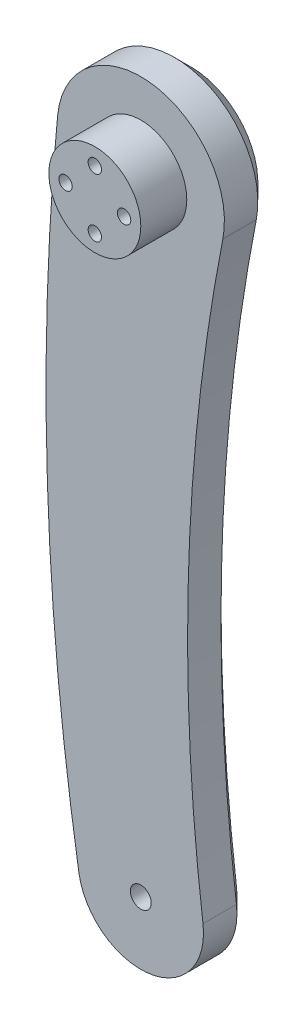
SolidWorks part; units mm, degrees
ref_plane "Front Plane" through (0, 0, 0) normal (0, 0, 1) x (1, 0, 0)
ref_plane "Top Plane" through (0, 0, 0) normal (0, 1, 0) x (1, 0, 0)
ref_plane "Right Plane" through (0, 0, 0) normal (1, 0, 0) x (0, 0, -1)
sketch "Sketch1" plane through (0, 0, 0) normal (0, 0, 1) x (1, 0, 0)
  arc A0 (-14.8033, -152.4209) -> (14.877, -148.0833) centre (0, -150) ccw
  arc A1 (19.625, -3.8546) -> (-19.9079, 1.9167) centre (0, 0) ccw
  arc A6 (-19.9079, 1.9167) -> (-14.8033, -152.4209) centre (577.3305, -55.5833) ccw
  arc A7 (19.625, -3.8546) -> (14.877, -148.0833) centre (461.1883, -90.5833) ccw
  point P8 (0, 0)
  point P9 (0, 0)
  point P10 (0, 0)
  point P11 (0, 0)
  dimension "D2" = 20
  dimension "D3" = 15
  dimension "D4" = 600
  dimension "D5" = 450
  dimension "D1" = 150
extrude "Boss-Extrude1" add sketch "Sketch1" along normal blind 12
chamfer "Chamfer1" distance 4 angle 45 4 edges at (-22.3416, -75.417, 0) (2.1691, -164.8423, 0) (11.432, -75.7774, 0) (2.8891, 19.7902, 0)
sketch "Sketch2" plane through (0, 0, 12) normal (0, 0, 1) x (1, 0, 0)
  circle A1 centre (0, 7) radius 1.6
  circle A2 centre (7, 0) radius 1.6
  circle A3 centre (0, -7) radius 1.6
  circle A4 centre (-7, 0) radius 1.6
  point P14 (0, 0)
  dimension "D2" = 14
  dimension "D3" = 3.2
  dimension "D1" = 4
extrude "Cut-Extrude1" cut sketch "Sketch2" against normal up to next
sketch "Sketch3" plane through (0, 0, 12) normal (0, 0, 1) x (1, 0, 0)
  circle A0 centre (0, -150) radius 2.5
  dimension "D1" = 5
extrude "Cut-Extrude2" cut sketch "Sketch3" against normal up to next
sketch "Sketch4" plane through (0, 0, 12) normal (0, 0, 1) x (1, 0, 0)
  circle A0 centre (0, 0) radius 11
  circle A1 centre (7, 0) radius 1.6 construction
  circle A2 centre (0, -7) radius 1.6 construction
  circle A3 centre (-7, 0) radius 1.6 construction
  circle A5 centre (0, 7) radius 1.6 construction
  circle A6 centre (7, 0) radius 1.6
  circle A7 centre (0, -7) radius 1.6
  circle A8 centre (-7, 0) radius 1.6
  circle A10 centre (0, 7) radius 1.6
  dimension "D1" = 22
extrude "Boss-Extrude2" add sketch "Sketch4" along normal blind 11
sketch "Sketch5" plane through (0, 0, 0) normal (0, 0, -1) x (-1, 0, 0)
  circle A0 centre (0, 7) radius 2.5
  circle A1 centre (7, 0) radius 2.5
  circle A2 centre (0, -7) radius 2.5
  circle A3 centre (-7, 0) radius 2.5
  dimension "D1" = 5
extrude "Cut-Extrude3" cut sketch "Sketch5" against normal blind 18
